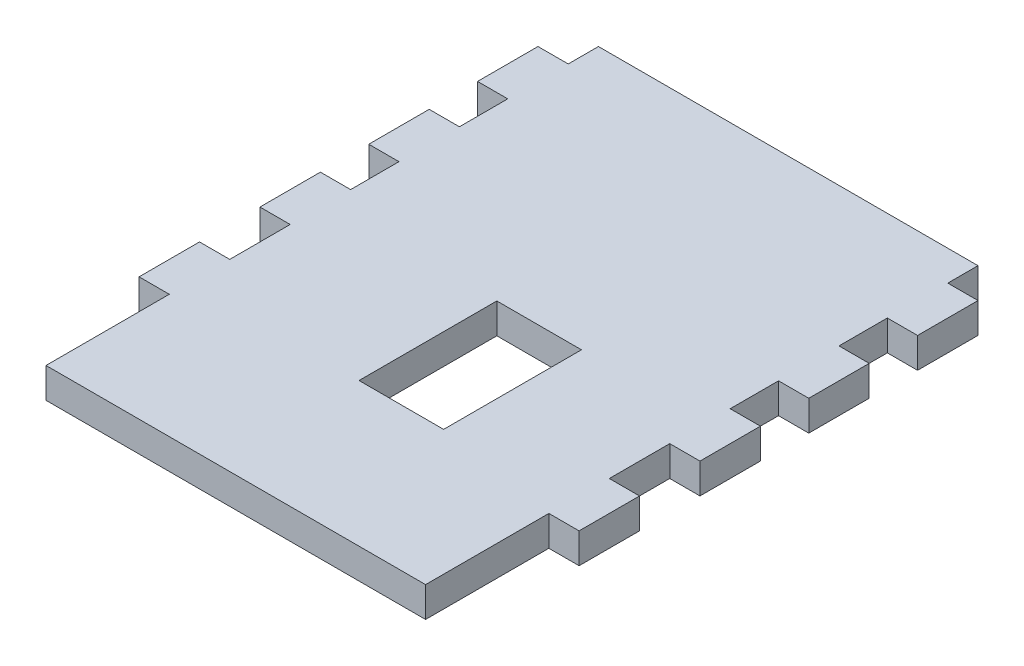
SolidWorks part; units mm, degrees
material "Maple"
ref_plane "Front Plane" through (0, 0, 0) normal (0, 0, 1) x (1, 0, 0)
ref_plane "Top Plane" through (0, 0, 0) normal (0, 1, 0) x (1, 0, 0)
ref_plane "Right Plane" through (0, 0, 0) normal (1, 0, 0) x (0, 0, -1)
sketch "Sketch1" plane through (0, 0, 0) normal (0, 1, 0) x (1, 0, 0)
  line L1 (0, 0) -> (46.228, 0)
  line L2 (0, 0) -> (0, 62.484)
  line L3 (0, 62.484) -> (46.228, 62.484)
  line L4 (46.228, 0) -> (46.228, 62.484)
  dimension "D1" = 46.228
  dimension "D2" = 62.484
extrude "Boss-Extrude1" add sketch "Sketch1" along normal blind 3.175
sketch "Sketch4" plane through (0, 3.175, 0) normal (0, 1, 0) x (1, 0, 0)
  line L0 (-1.7463, 0) -> (1.7463, 0) construction
  line L1 (46.228, 0) -> (43.053, 0)
  line L2 (46.228, 0) -> (46.228, 12.954)
  line L3 (46.228, 12.954) -> (43.053, 12.954)
  line L4 (43.053, 0) -> (43.053, 12.954)
  line L5 (46.228, 0) -> (46.228, 62.484) construction
  line L7 (46.228, 32.004) -> (43.053, 32.004)
  line L8 (46.228, 32.004) -> (46.228, 37.084)
  line L9 (46.228, 37.084) -> (43.053, 37.084)
  line L10 (43.053, 32.004) -> (43.053, 37.084)
  line L11 (46.228, 43.434) -> (43.053, 43.434)
  line L12 (46.228, 43.434) -> (46.228, 48.514)
  line L13 (46.228, 48.514) -> (43.053, 48.514)
  line L14 (43.053, 43.434) -> (43.053, 48.514)
  line L15 (46.228, 54.864) -> (43.053, 54.864)
  line L16 (46.228, 54.864) -> (46.228, 62.484)
  line L17 (46.228, 62.484) -> (43.053, 62.484)
  line L18 (43.053, 54.864) -> (43.053, 62.484)
  line L23 (46.228, 62.484) -> (0, 62.484) construction
  line L24 (23.114, 62.484) -> (23.114, 0) construction
  line L25 (46.228, 25.654) -> (43.053, 25.654)
  line L26 (46.228, 25.654) -> (46.228, 19.304)
  line L27 (46.228, 19.304) -> (43.053, 19.304)
  line L28 (43.053, 25.654) -> (43.053, 19.304)
  line L29 (0, 12.954) -> (3.175, 12.954)
  line L30 (3.175, 0) -> (3.175, 12.954)
  line L31 (0, 0) -> (3.175, 0)
  line L32 (0, 0) -> (0, 12.954)
  line L33 (0, 19.304) -> (3.175, 19.304)
  line L34 (3.175, 25.654) -> (3.175, 19.304)
  line L35 (0, 25.654) -> (3.175, 25.654)
  line L36 (0, 25.654) -> (0, 19.304)
  line L37 (0, 37.084) -> (3.175, 37.084)
  line L38 (3.175, 32.004) -> (3.175, 37.084)
  line L39 (0, 32.004) -> (3.175, 32.004)
  line L40 (0, 32.004) -> (0, 37.084)
  line L41 (0, 48.514) -> (3.175, 48.514)
  line L42 (3.175, 43.434) -> (3.175, 48.514)
  line L43 (0, 43.434) -> (3.175, 43.434)
  line L44 (0, 43.434) -> (0, 48.514)
  line L45 (0, 62.484) -> (3.175, 62.484)
  line L46 (3.175, 54.864) -> (3.175, 62.484)
  line L47 (0, 54.864) -> (3.175, 54.864)
  line L48 (0, 54.864) -> (0, 62.484)
  line L50 (20.9882, 29.5512) -> (29.8782, 29.5512)
  line L51 (20.9882, 29.5512) -> (20.9882, 15.0732)
  line L52 (20.9882, 15.0732) -> (29.8782, 15.0732)
  line L53 (29.8782, 29.5512) -> (29.8782, 15.0732)
  dimension "D1" = 7.62
  dimension "D2" = 3.175
  dimension "D3" = 3.175
  dimension "D4" = 6.35
  dimension "D5" = 5.08
  dimension "D6" = 6.35
  dimension "D7" = 5.08
  dimension "D8" = 6.35
  dimension "D9" = 6.35
  dimension "D10" = 6.35
  dimension "D11" = 14.478
  dimension "D12" = 8.89
extrude "Cut-Extrude2" cut sketch "Sketch4" against normal blind 4.064
sketch "Sketch5" plane through (0, 3.175, 0) normal (0, 1, 0) x (1, 0, 0)
  line L0 (43.053, 62.484) -> (43.053, 54.864) construction
  line L1 (3.175, 62.484) -> (43.053, 62.484)
  line L2 (3.175, 62.484) -> (3.175, 58.039)
  line L3 (3.175, 58.039) -> (43.053, 58.039)
  line L4 (43.053, 62.484) -> (43.053, 58.039)
  dimension "D1" = 4.445
extrude "Cut-Extrude3" cut sketch "Sketch5" against normal blind 4.064
